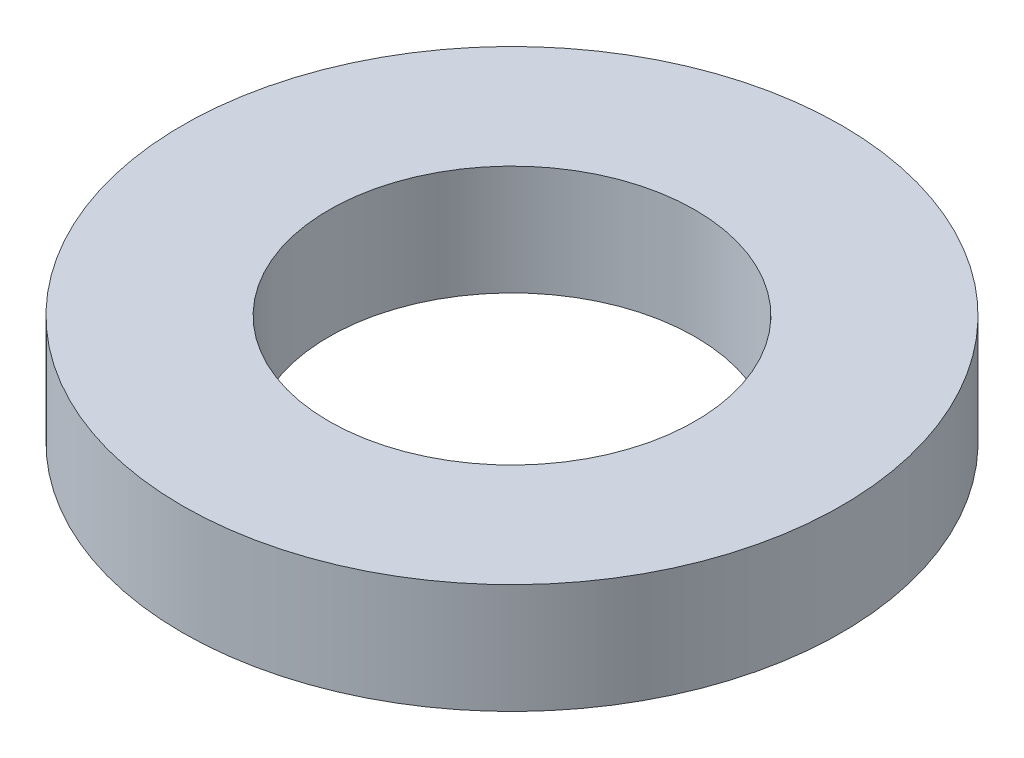
SolidWorks part; units mm, degrees
ref_plane "前视基准面" through (0, 0, 0) normal (0, 0, 1) x (1, 0, 0)
ref_plane "上视基准面" through (0, 0, 0) normal (0, 1, 0) x (1, 0, 0)
ref_plane "右视基准面" through (0, 0, 0) normal (1, 0, 0) x (0, 0, -1)
sketch "草图1" plane through (0, 0, 0) normal (0, 1, 0) x (1, 0, 0)
  circle A0 centre (0, 0) radius 9
  circle A1 centre (0, 0) radius 5
  dimension "D1" = 18
  dimension "D2" = 10
extrude "凸台-拉伸1" add sketch "草图1" along normal blind 3
